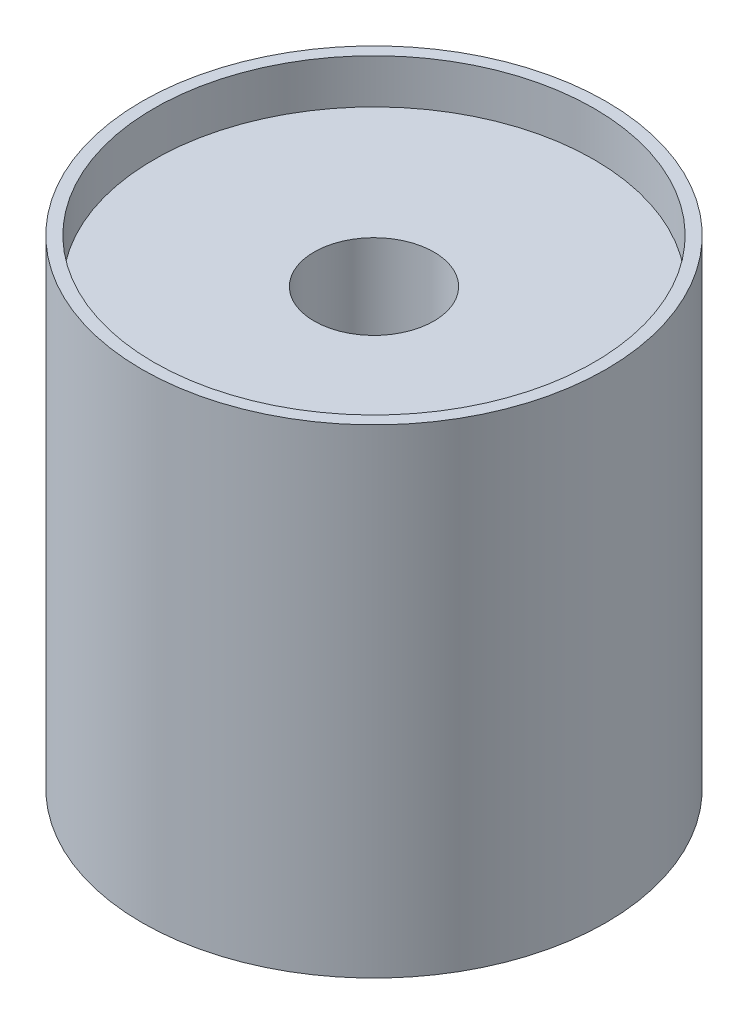
SolidWorks part; units mm, degrees
material "HYPALON"
ref_plane "Front Plane" through (0, 0, 0) normal (0, 0, 1) x (1, 0, 0)
ref_plane "Top Plane" through (0, 0, 0) normal (0, 1, 0) x (1, 0, 0)
ref_plane "Right Plane" through (0, 0, 0) normal (1, 0, 0) x (0, 0, -1)
sketch "Sketch1" plane through (0, 0, 0) normal (0, 1, 0) x (1, 0, 0)
  circle A1 centre (0, 0) radius 49.2125
extrude "Boss-Extrude1" add sketch "Sketch1" along normal blind 101.6
sketch "Sketch2" plane through (0, 101.6, 0) normal (0, 1, 0) x (1, 0, 0)
  circle A0 centre (0, 0) radius 12.7
extrude "Cut-Extrude1" cut sketch "Sketch2" against normal blind 45.72
sketch "Sketch3" plane through (0, 101.6, 0) normal (0, 1, 0) x (1, 0, 0)
  circle A0 centre (0, 0) radius 46.6543
extrude "Cut-Extrude2" cut sketch "Sketch3" against normal blind 9.398
